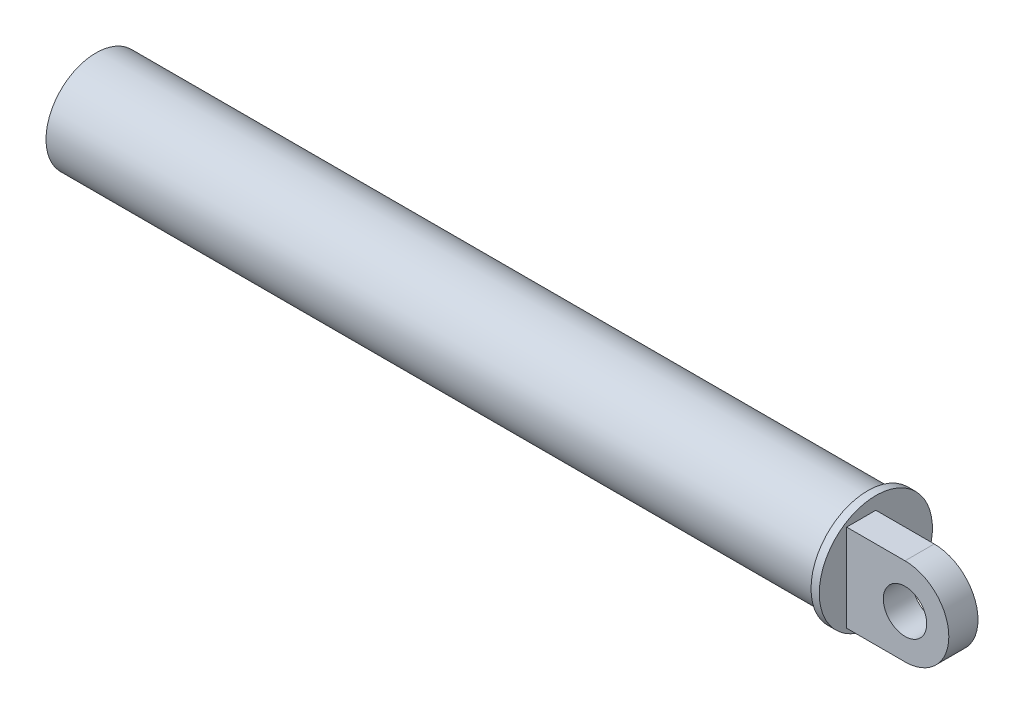
SolidWorks part; units mm, degrees
ref_plane "Front Plane" through (0, 0, 0) normal (0, 0, 1) x (1, 0, 0)
ref_plane "Top Plane" through (0, 0, 0) normal (0, 1, 0) x (1, 0, 0)
ref_plane "Right Plane" through (0, 0, 0) normal (1, 0, 0) x (0, 0, -1)
sketch "Sketch1" plane through (0, 0, 0) normal (0, 0, 1) x (1, 0, 0)
  line L1 (333.8532, 48.613) -> (353.8532, 48.613)
  line L2 (333.8532, 48.613) -> (333.8532, 18.613)
  line L3 (333.8532, 18.613) -> (353.8532, 18.613)
  circle A0 centre (353.8532, 33.613) radius 7.4396
  arc A1 (353.8532, 18.613) -> (353.8532, 48.613) centre (353.8532, 33.613) ccw
  dimension "D1" = 30
  dimension "D2" = 20
extrude "Boss-Extrude1" add sketch "Sketch1" along normal blind 10
sketch "Sketch2" plane through (0, 0, 0) normal (0, 0, 1) x (1, 0, 0)
  line L1 (333.8532, 48.613) -> (333.8532, 52.9936)
  line L9 (353.8532, 48.613) -> (333.8532, 48.613) construction
  line L11 (333.8532, 48.613) -> (333.8532, 18.613) construction
  line L12 (333.8532, 52.9936) -> (331.0264, 52.9936)
  line L13 (331.0264, 52.9936) -> (331.0264, 50.7427)
  line L14 (331.0264, 50.7427) -> (66.6711, 50.7427)
  line L15 (66.6711, 50.7427) -> (66.6711, 42.2992)
  line L16 (66.6711, 42.2992) -> (318.5593, 42.2992)
  line L17 (318.5593, 42.2992) -> (318.5593, 33.613)
  line L18 (318.5593, 33.613) -> (333.8532, 33.613)
  line L20 (333.8532, 33.613) -> (333.8532, 48.613)
  point P11 (54.8445, 50.7427)
revolve "Revolve2" add sketch "Sketch2" angle 360 about L18
